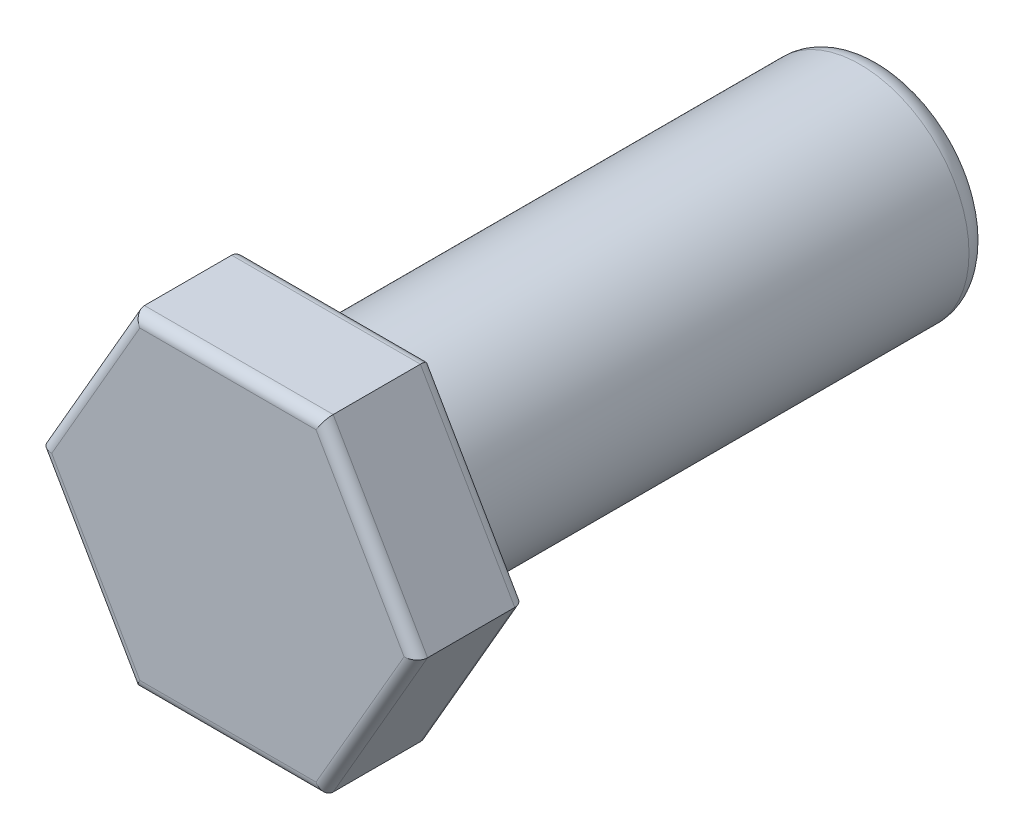
SolidWorks part; units mm, degrees
ref_plane "前视" through (0, 0, 0) normal (0, 0, 1) x (1, 0, 0)
ref_plane "上视" through (0, 0, 0) normal (0, 1, 0) x (1, 0, 0)
ref_plane "右视" through (0, 0, 0) normal (1, 0, 0) x (0, 0, -1)
sketch "草图1" plane through (0, 0, 0) normal (0, 0, 1) x (1, 0, 0)
  circle A0 centre (0, 0) radius 5
  dimension "D1" = 10
extrude "凸台-拉伸1" add sketch "草图1" along normal blind 25
sketch "草图2" plane through (0, 0, 25) normal (0, 0, 1) x (1, 0, 0)
  line L1 (4.3301, -7.5) -> (8.6603, 0)
  line L2 (8.6603, 0) -> (4.3301, 7.5)
  line L3 (4.3301, 7.5) -> (-4.3301, 7.5)
  line L4 (-4.3301, 7.5) -> (-8.6603, 0)
  line L5 (-8.6603, 0) -> (-4.3301, -7.5)
  line L6 (-4.3301, -7.5) -> (4.3301, -7.5)
  circle A0 centre (0, 0) radius 7.5 construction
  dimension "D1" = 15
extrude "凸台-拉伸2" add sketch "草图2" along normal blind 5
fillet "圆角1" radius 1 1 edges at (5, 0, 0)
fillet "圆角2" radius 0.5 12 edges at (6.4952, -3.75, 25) (0, -7.5, 25) (-6.4952, -3.75, 25) (6.4952, 3.75, 25) (0, 7.5, 30) (-6.4952, 3.75, 30) (0, 7.5, 25) (-6.4952, 3.75, 25) (6.4952, -3.75, 30) (6.4952, 3.75, 30) (-6.4952, -3.75, 30) (0, -7.5, 30)
